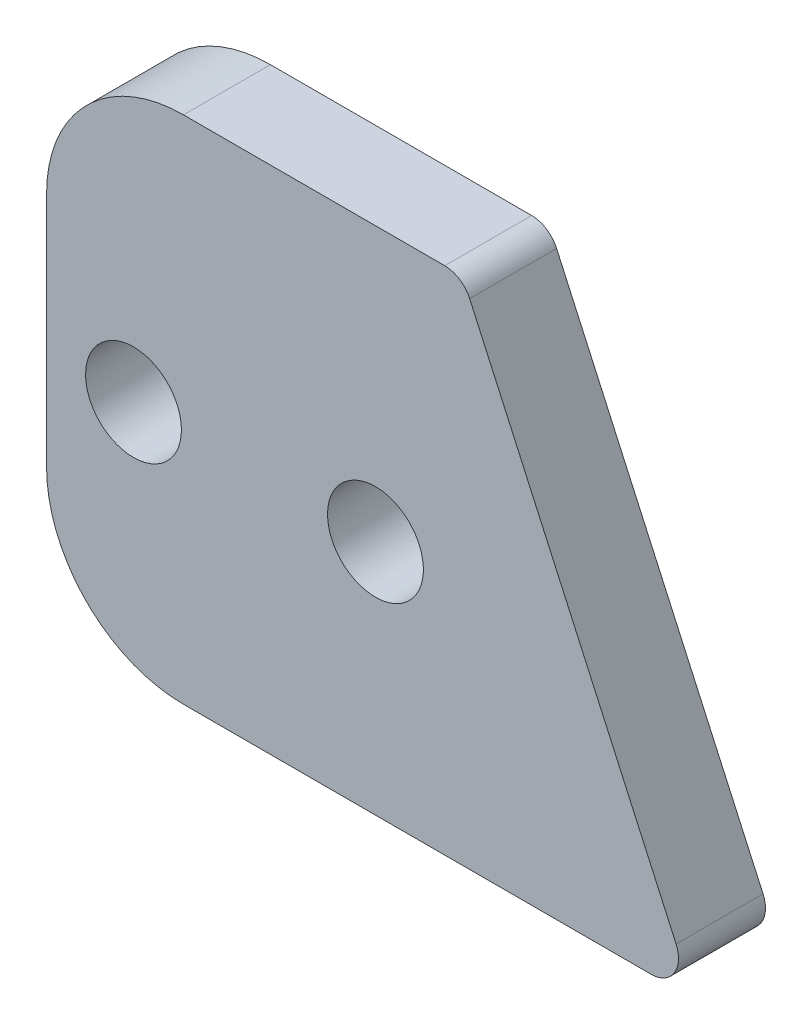
SolidWorks part; units mm, degrees
ref_plane "Front Plane" through (0, 0, 0) normal (0, 0, 1) x (1, 0, 0)
ref_plane "Top Plane" through (0, 0, 0) normal (0, 1, 0) x (1, 0, 0)
ref_plane "Right Plane" through (0, 0, 0) normal (1, 0, 0) x (0, 0, -1)
sketch "Sketch1" plane through (0, 0, 0) normal (0, 0, 1) x (1, 0, 0)
  line L0 (11.8154, -9.3209) -> (3.3704, 9.3209)
  line L1 (-11.8154, 9.3209) -> (11.8154, 9.3209) construction
  line L2 (-11.8154, 9.3209) -> (-11.8154, -9.3209)
  line L3 (-11.8154, -9.3209) -> (11.8154, -9.3209)
  line L4 (11.8154, 9.3209) -> (11.8154, -9.3209) construction
  line L5 (0, -9.3209) -> (0, 9.3209) construction
  line L6 (-11.8154, 0) -> (11.8154, 0) construction
  line L7 (3.3704, 9.3209) -> (-11.8154, 9.3209)
  point P0 (0, 0)
  dimension "D1" = 65.629
  dimension "D2" = 18.6418
  dimension "D3" = 23.6308
extrude "Boss-Extrude1" add sketch "Sketch1" along normal mid plane 3.175
sketch "Sketch2" plane through (0, 0, 1.5875) normal (0, 0, 1) x (1, 0, 0)
  line L1 (-4.2225, 9.3209) -> (-4.2225, -9.3209) construction
  line L2 (3.3704, 9.3209) -> (3.3704, -9.3209) construction
  line L3 (-11.8154, -9.3209) -> (11.8154, -9.3209) construction
  line L5 (3.3704, 9.3209) -> (-11.8154, 9.3209) construction
  circle A0 centre (0.1954, -0.6791) radius 1.75
  circle A2 centre (-8.6404, -0.6791) radius 1.75
  dimension "D1" = 12.0108
  dimension "D2" = 3.5
  dimension "D3" = 0.6791
extrude "Cut-Extrude1" cut sketch "Sketch2" against normal through all both and the other way through all
fillet "Fillet1" radius 1 2 edges at (3.3704, 9.3209, 0) (11.8154, -9.3209, 0)
fillet "Fillet2" radius 5 2 edges at (-11.8154, 9.3209, 0) (-11.8154, -9.3209, 0)
